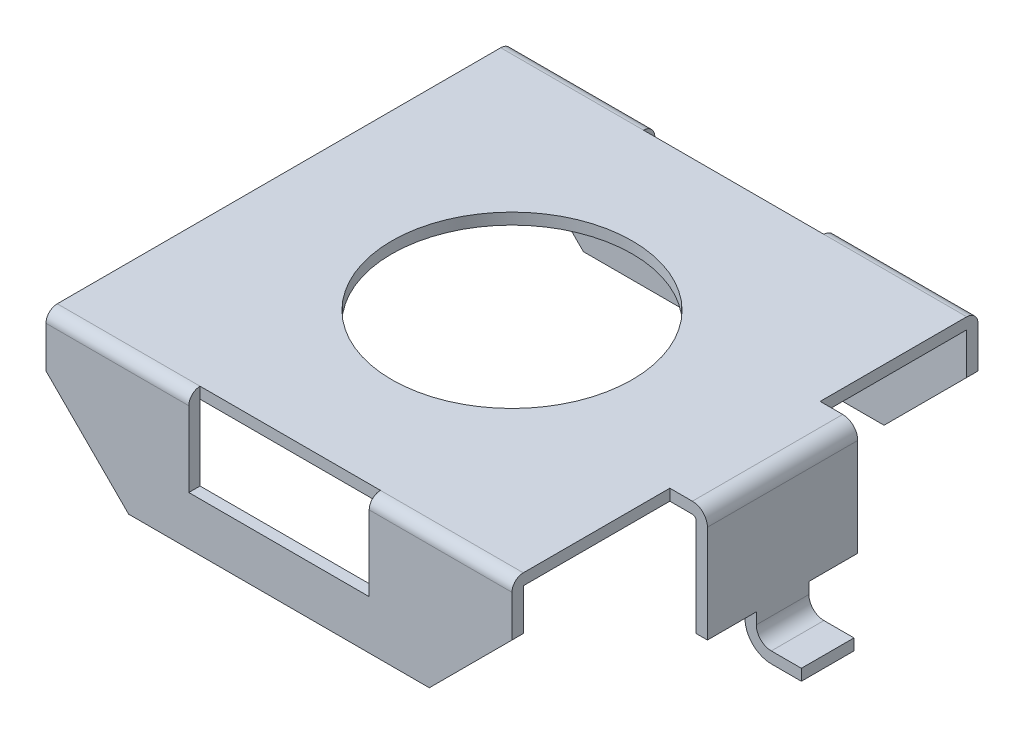
SolidWorks part; units mm, degrees
ref_plane "Front Plane" through (0, 0, 0) normal (0, 0, 1) x (1, 0, 0)
ref_plane "Top Plane" through (0, 0, 0) normal (0, 1, 0) x (1, 0, 0)
ref_plane "Right Plane" through (0, 0, 0) normal (1, 0, 0) x (0, 0, -1)
sketch "Sketch1" plane through (0, 0, 0) normal (1, 0, 0) x (0, 0, -1)
  line L0 (-3.1, 0.2) -> (-3.1, 2)
  line L1 (-3.1, 2) -> (3.1, 2)
  line L2 (3.1, 2) -> (3.1, 0.2)
  point P2 (0, 2)
  dimension "D1" = 2
  dimension "D2" = 1.8
  dimension "D3" = 6.2
extrude "Extrude-Thin1" add sketch "Sketch1" along normal mid plane 6.2 thin
sketch "Sketch3" plane through (0, 0, 0) normal (0, 0, 1) x (1, 0, 0)
  line L0 (0, 0) -> (0, 3.2778) construction
  line L1 (-3.1, 1.3) -> (-3.1, 0.2)
  line L2 (-3.1, 0.2) -> (-3.1, 2) construction
  line L3 (-3.1, 0.2) -> (-2, 0.2)
  line L4 (3.1, 0.2) -> (-3.1, 0.2) construction
  line L5 (-2, 0.2) -> (-3.1, 1.3)
  line L6 (2, 0.2) -> (3.1, 0.2)
  line L7 (3.1, 0.2) -> (3.1, 1.3)
  line L8 (3.1, 0.2) -> (3.1, 2) construction
  line L9 (3.1, 1.3) -> (2, 0.2)
  line L10 (3.1, 2) -> (-3.1, 2) construction
  line L11 (-1.2, 1.85) -> (1.2, 1.85)
  line L12 (-1.2, 1.85) -> (-1.2, 0.85)
  line L13 (-1.2, 0.85) -> (1.2, 0.85)
  line L14 (1.2, 1.85) -> (1.2, 0.85)
  line L15 (-1.2, 1.85) -> (1.2, 0.85) construction
  line L16 (-1.2, 0.85) -> (1.2, 1.85) construction
  line L17 (3.1, 2) -> (-3.1, 2) construction
  point P14 (0, 1.35)
  point P22 (0, 0)
  point P23 (2, 0.2)
  point P24 (3.1, 1.2486)
  point P25 (0, 1.2673)
  dimension "D1" = 1
  dimension "D2" = 2.4
  dimension "D3" = 4
  dimension "D4" = 0.15
extrude "Cut-Extrude1" cut sketch "Sketch3" against normal through all both and the other way through all
sketch "Sketch4" plane through (0, 2, 0) normal (0, 1, 0) x (1, 0, 0)
  line L0 (1.2, 2.95) -> (1.2, 3.1) construction
  line L1 (1.2, 3.1) -> (-1.2, 3.1) construction
  line L2 (-1.2, 3.1) -> (-1.2, 2.95) construction
  line L3 (-1.2, 2.95) -> (1.2, 2.95) construction
  line L4 (-1.2, -2.95) -> (-1.2, -3.1) construction
  line L5 (-1.2, -3.1) -> (1.2, -3.1) construction
  line L6 (1.2, -3.1) -> (1.2, -2.95) construction
  line L7 (1.2, -2.95) -> (-1.2, -2.95) construction
  line L8 (1.2, 2.95) -> (1.2, 3.1)
  line L9 (1.2, 3.1) -> (-1.2, 3.1)
  line L10 (-1.2, 3.1) -> (-1.2, 2.95)
  line L11 (-1.2, 2.95) -> (1.2, 2.95)
  line L12 (-1.2, -2.95) -> (-1.2, -3.1)
  line L13 (-1.2, -3.1) -> (1.2, -3.1)
  line L14 (1.2, -3.1) -> (1.2, -2.95)
  line L15 (1.2, -2.95) -> (-1.2, -2.95)
  circle A0 centre (0, 0) radius 1.6
  dimension "D1" = 3.2
extrude "Cut-Extrude2" cut sketch "Sketch4" against normal up to surface (0.15 mm away) up to face at (0, 1.85, 0)
fillet "Fillet1" radius 0.15 4 edges at (2.15, 2, 3.1) (-2.15, 2, 3.1) (2.15, 2, -3.1) (-2.15, 2, -3.1)
sketch "Sketch5" plane through (0, 0, 0) normal (0, 0, 1) x (1, 0, 0)
  line L0 (4.2, 0.15) -> (3.8, 0.15)
  line L1 (3.1, 2) -> (3.4, 2)
  line L2 (3.6, 1.8) -> (3.6, 0.35)
  arc A0 (3.8, 0.15) -> (3.6, 0.35) centre (3.8, 0.35) cw
  arc A1 (3.4, 2) -> (3.6, 1.8) centre (3.4, 1.8) cw
  dimension "D4" = 0.2
  dimension "D1" = 0.15
  dimension "D2" = 3.6
  dimension "D3" = 4.2
extrude "Extrude-Thin2" add sketch "Sketch5" along normal mid plane 2 thin thin type one direction wall 0.15
sketch "Sketch6" plane through (0, 0, 0) normal (0, -1, 0) x (1, 0, 0)
  line L0 (4.2, 1) -> (4.2, -1) construction
  line L1 (3.2, 1.35) -> (4.2, 1.35)
  line L2 (3.2, 1.35) -> (3.2, 0.35)
  line L3 (3.2, 0.35) -> (4.2, 0.35)
  line L4 (4.2, 1.35) -> (4.2, 0.35)
  line L5 (3.2, 1.35) -> (4.2, 0.35) construction
  line L6 (3.2, 0.35) -> (4.2, 1.35) construction
  line L7 (3.2, -0.35) -> (4.2, -0.35)
  line L8 (3.2, -0.35) -> (3.2, -1.35)
  line L9 (3.2, -1.35) -> (4.2, -1.35)
  line L10 (4.2, -0.35) -> (4.2, -1.35)
  line L11 (3.2, -0.35) -> (4.2, -1.35) construction
  line L12 (3.2, -1.35) -> (4.2, -0.35) construction
  line L13 (3.7, -0.85) -> (3.7, 0.85) construction
  point P0 (3.7, 0.85)
  point P5 (3.7, -0.85)
  point P10 (3.7, 0)
  dimension "D1" = 1
  dimension "D2" = 1
  dimension "D3" = 0.7
extrude "Cut-Extrude3" cut sketch "Sketch6" against normal blind 0.5
